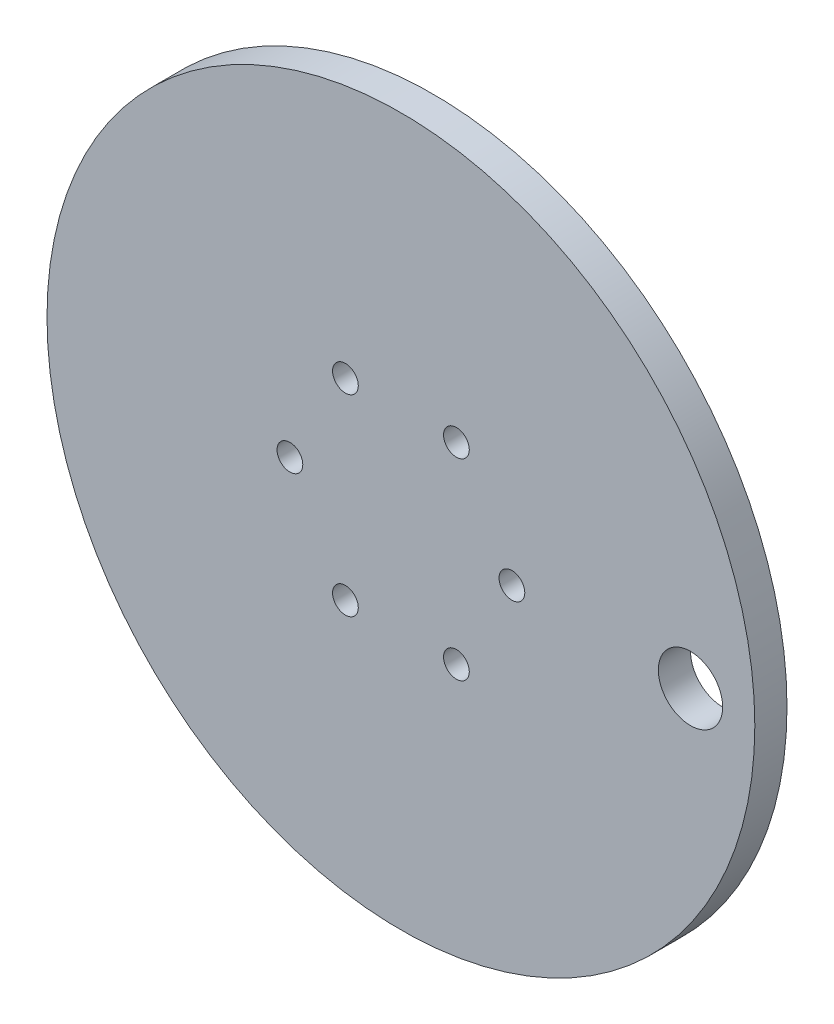
SolidWorks part; units mm, degrees
ref_plane "前视基准面" through (0, 0, 0) normal (0, 0, 1) x (1, 0, 0)
ref_plane "上视基准面" through (0, 0, 0) normal (0, 1, 0) x (1, 0, 0)
ref_plane "右视基准面" through (0, 0, 0) normal (1, 0, 0) x (0, 0, -1)
sketch "草图1" plane through (0, 0, 0) normal (0, 0, 1) x (1, 0, 0)
  circle A0 centre (0, 0) radius 22.5
  dimension "D1" = 45
extrude "凸台-拉伸1" add sketch "草图1" along normal blind 5
sketch "草图2" plane through (0, 0, 5) normal (0, 0, 1) x (1, 0, 0)
  circle A0 centre (0, 0) radius 17.25 construction
  circle A1 centre (17.25, 0) radius 2
  circle A2 centre (8.625, -14.9389) radius 2
  circle A3 centre (-8.625, -14.9389) radius 2
  circle A4 centre (-17.25, 0) radius 2
  circle A5 centre (-8.625, 14.9389) radius 2
  circle A6 centre (8.625, 14.9389) radius 2
  point P17 (0, 0)
  dimension "D1" = 34.5
  dimension "D2" = 4
  dimension "D3" = 6
extrude "切除-拉伸1" cut sketch "草图2" against normal through all
sketch "草图3" plane through (0, 0, 5) normal (0, 0, 1) x (1, 0, 0)
  circle A0 centre (0, 0) radius 55
  dimension "D1" = 110
extrude "凸台-拉伸2" add sketch "草图3" along normal blind 5
sketch "草图4" plane through (0, 0, 10) normal (0, 0, 1) x (1, 0, 0)
  circle A0 centre (0, 0) radius 45
  circle A1 centre (45, 0) radius 5
  dimension "D1" = 90
  dimension "D2" = 10
extrude "切除-拉伸2" cut sketch "草图4" against normal through all contours A0 A1 | A0 A1
sketch "草图5" plane through (0, 0, 5) normal (0, 0, -1) x (-1, 0, 0)
  circle A0 centre (8.625, 14.9389) radius 2 construction
  circle A1 centre (0, 0) radius 22.5
  circle A2 centre (0, 0) radius 22.5
  circle A3 centre (17.25, 0) radius 2 construction
  circle A4 centre (8.625, -14.9389) radius 2 construction
  circle A5 centre (-8.625, -14.9389) radius 2 construction
  circle A6 centre (-17.25, 0) radius 2 construction
  circle A7 centre (-8.625, 14.9389) radius 2 construction
  circle A8 centre (-8.625, 14.9389) radius 2
  circle A9 centre (-17.25, 0) radius 2
  circle A10 centre (-8.625, -14.9389) radius 2
  circle A11 centre (8.625, -14.9389) radius 2
  circle A12 centre (17.25, 0) radius 2
  circle A13 centre (8.625, 14.9389) radius 2
  dimension "D1" = 0
extrude "切除-拉伸3" cut sketch "草图5" against normal through all contours A9 | A8 | A13 | A11 | A10 | A12
